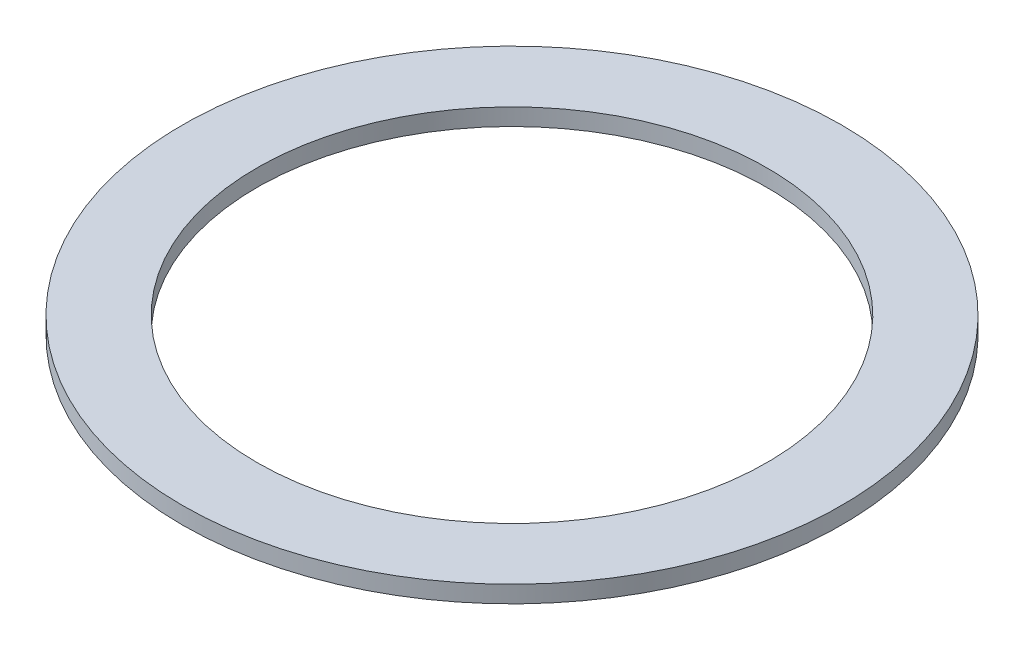
SolidWorks part; units mm, degrees
material "Copper"
ref_plane "Front Plane" through (0, 0, 0) normal (0, 0, 1) x (1, 0, 0)
ref_plane "Top Plane" through (0, 0, 0) normal (0, 1, 0) x (1, 0, 0)
ref_plane "Right Plane" through (0, 0, 0) normal (1, 0, 0) x (0, 0, -1)
sketch "Sketch1" plane through (0, 0, 0) normal (0, 1, 0) x (1, 0, 0)
  circle A0 centre (0, 0) radius 77.5
  circle A1 centre (0, 0) radius 60
  dimension "D1" = 155
  dimension "D2" = 120
extrude "Boss-Extrude1" add sketch "Sketch1" along normal blind 4
